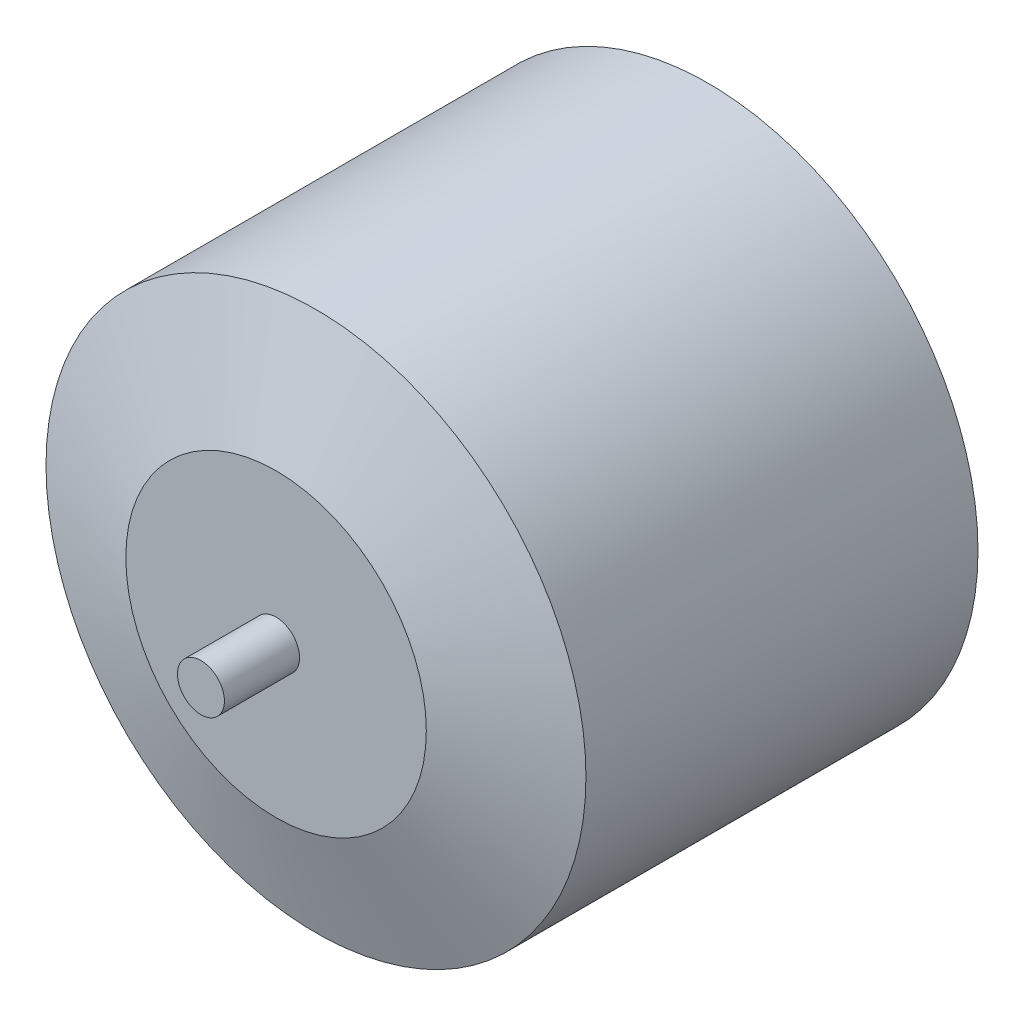
SolidWorks part; units mm, degrees
ref_plane "Front Plane" through (0, 0, 0) normal (0, 0, 1) x (1, 0, 0)
ref_plane "Top Plane" through (0, 0, 0) normal (0, 1, 0) x (1, 0, 0)
ref_plane "Right Plane" through (0, 0, 0) normal (1, 0, 0) x (0, 0, -1)
sketch "Sketch1" plane through (0, 0, 0) normal (0, 0, 1) x (1, 0, 0)
  circle A0 centre (0, 0) radius 1
  dimension "D1" = 2
extrude "Boss-Extrude1" add sketch "Sketch1" against normal blind 3.2
sketch "Sketch2" plane through (0, 0, 0) normal (0, 1, 0) x (1, 0, 0)
  line L0 (0, 3.2) -> (0, 21.6)
  line L1 (1, 3.2) -> (-1, 3.2) construction
  line L2 (0, 21.6) -> (-11.5, 21.6)
  line L3 (-11.5, 21.6) -> (-11.5, 4.9)
  line L4 (-11.5, 4.9) -> (-6.4, 3.2)
  line L5 (-6.4, 3.2) -> (0, 3.2)
  point P5 (-16.7, 8.6532)
  dimension "D1" = 18.4
  dimension "D2" = 11.5
  dimension "D3" = 6.4
  dimension "D4" = 16.7
revolve "Revolve1" add sketch "Sketch2" angle 360 about L0
